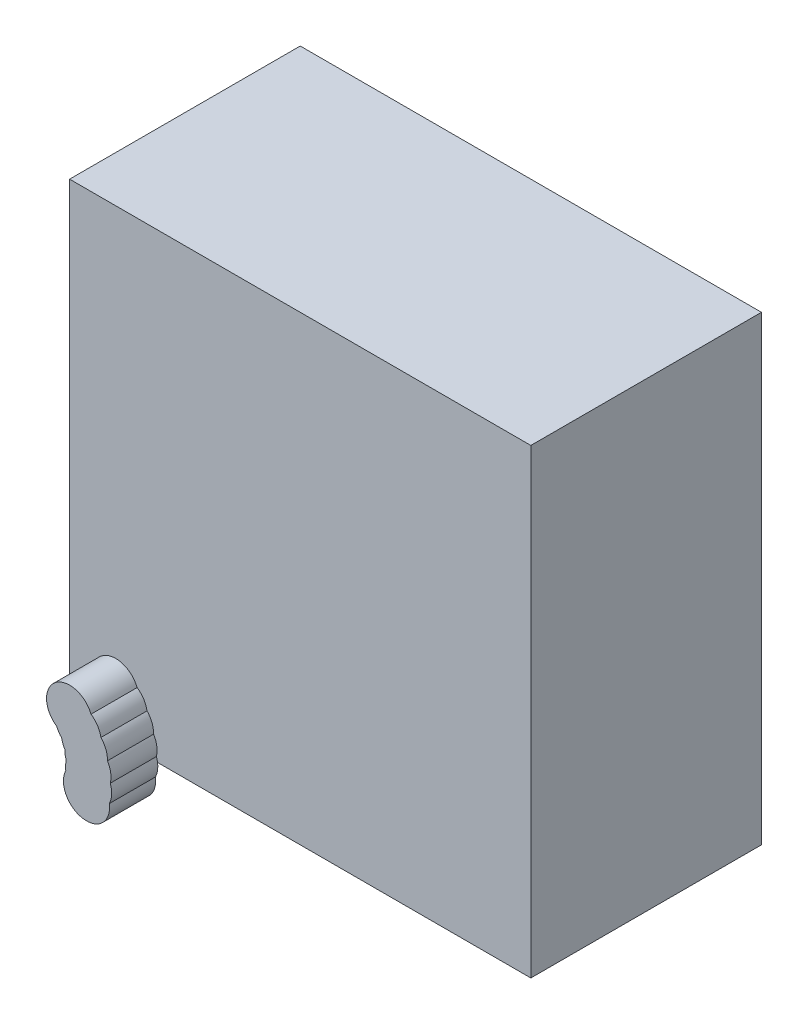
SolidWorks part; units mm, degrees
ref_plane "前视基准面" through (0, 0, 0) normal (0, 0, 1) x (1, 0, 0)
ref_plane "上视基准面" through (0, 0, 0) normal (0, 1, 0) x (1, 0, 0)
ref_plane "右视基准面" through (0, 0, 0) normal (1, 0, 0) x (0, 0, -1)
other "Configuration Table"
sketch "草图1" plane through (0, 0, 0) normal (0, 0, 1) x (1, 0, 0)
  line L1 (0, 0) -> (20, 0)
  line L2 (0, 0) -> (0, 20)
  line L3 (0, 20) -> (20, 20)
  line L4 (20, 0) -> (20, 20)
extrude "BaseBox" add sketch "草图1" along normal blind 10
sketch "草图2" plane through (0, 0, 10) normal (0, 0, 1) x (1, 0, 0)
  circle A0 centre (2, 2) radius 1
extrude "BossSeed" add sketch "草图2" along normal blind 2
pattern_circular "CircularPattern" count 6 every 12 about axis through (0, 0, 0) along (0, 0, 1) of "BossSeed"
